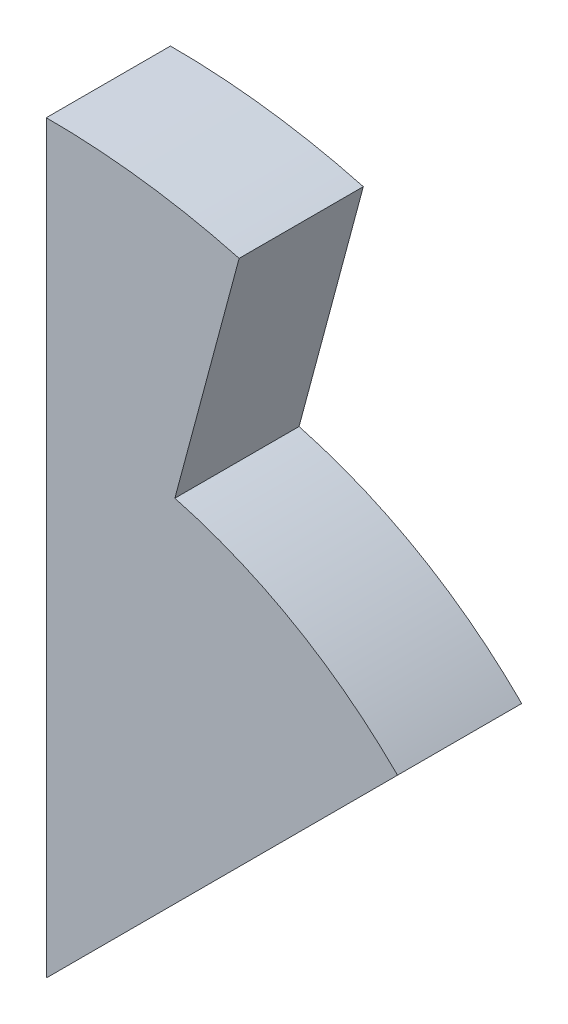
SolidWorks part; units mm, degrees
ref_plane "Ebene vorne" through (0, 0, 0) normal (0, 0, 1) x (1, 0, 0)
ref_plane "Ebene oben" through (0, 0, 0) normal (0, 1, 0) x (1, 0, 0)
ref_plane "Ebene rechts" through (0, 0, 0) normal (1, 0, 0) x (0, 0, -1)
sketch "Skizze1" plane through (0, 0, 0) normal (0, 0, 1) x (1, 0, 0)
  line L0 (0, 0) -> (0, 30)
  line L1 (0, 0) -> (21.2132, 21.2132)
  arc A0 (21.2132, 21.2132) -> (0, 30) centre (0, 0) ccw
  dimension "D2" = 60
  dimension "D1" = 45
extrude "Aufsatz-Linear austragen2" add sketch "Skizze1" along normal blind 5
sketch "Skizze2" plane through (0, 0, 5) normal (0, 0, 1) x (1, 0, 0)
  line L0 (0, 30) -> (0, 20) construction
  line L1 (0, 30) -> (0, 0) construction
  line L2 (0, 0) -> (7.7646, 28.9778) construction
  line L3 (14.1421, 14.1421) -> (21.2132, 21.2132)
  line L4 (0, 0) -> (21.2132, 21.2132) construction
  line L5 (5.1764, 19.3185) -> (7.7646, 28.9778)
  circle A0 centre (0, 0) radius 30 construction
  circle A1 centre (0, 0) radius 20 construction
  arc A2 (21.2132, 21.2132) -> (7.7646, 28.9778) centre (0, 0) ccw
  arc A3 (14.1421, 14.1421) -> (5.1764, 19.3185) centre (0, 0) ccw
  dimension "D1" = 40
  dimension "D2" = 60
  dimension "D3" = 15
extrude "Schnitt-Linear austragen2" cut sketch "Skizze2" against normal through all
